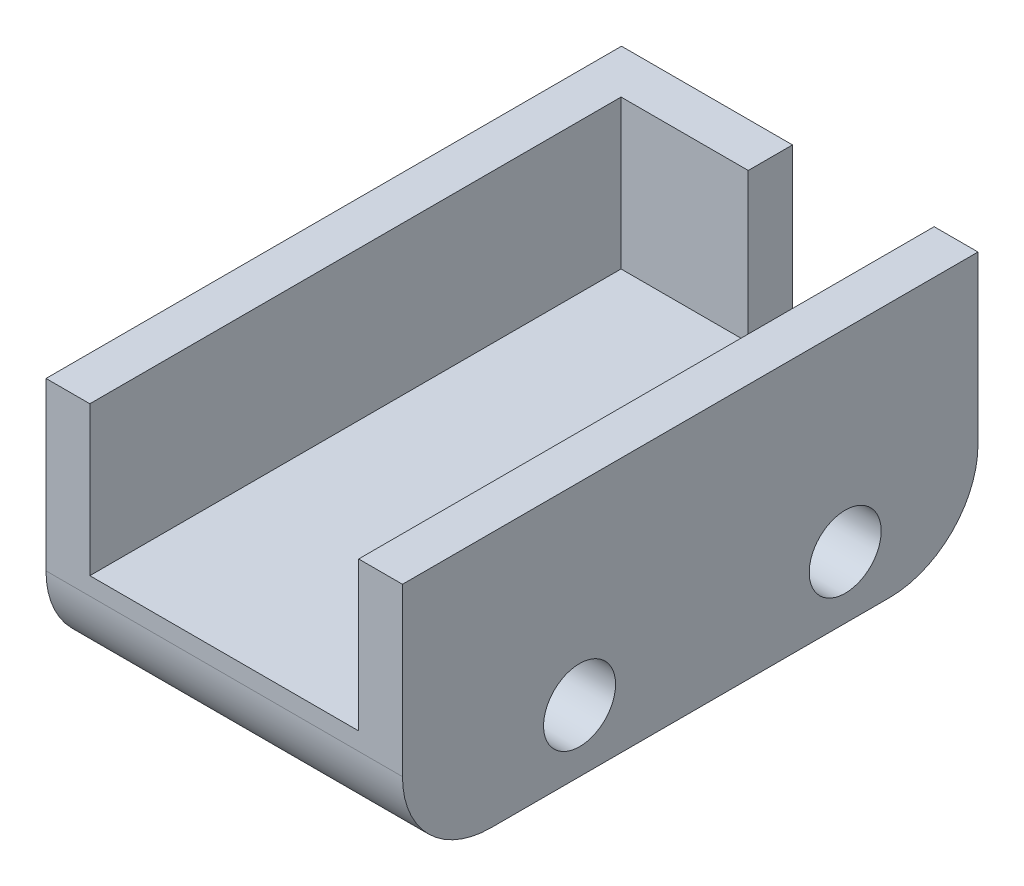
SolidWorks part; units mm, degrees
ref_plane "Plan de face" through (0, 0, 0) normal (0, 0, 1) x (1, 0, 0)
ref_plane "Plan de dessus" through (0, 0, 0) normal (0, 1, 0) x (1, 0, 0)
ref_plane "Plan de droite" through (0, 0, 0) normal (1, 0, 0) x (0, 0, -1)
sketch "Esquisse1" plane through (0, 0, 0) normal (0, 0, 1) x (1, 0, 0)
  line L1 (0, 0) -> (40.263, 0)
  line L2 (0, 0) -> (0, 26.8179)
  line L3 (0, 26.8179) -> (40.263, 26.8179)
  line L4 (40.263, 0) -> (40.263, 26.8179)
  dimension "D1" = 40.263
  dimension "D2" = 26.8179
extrude "Boss.-Extru.1" add sketch "Esquisse1" along normal blind 65 contours L2 L1 L4 L3
shell "Coque1" thickness 1.5
sketch "Esquisse4" plane through (0, 0, 0) normal (0, -1, 0) x (1, 0, 0)
  line L1 (0, 65) -> (40.263, 65)
  line L2 (0, 65) -> (0, 0)
  line L3 (0, 0) -> (40.263, 0)
  line L4 (40.263, 65) -> (40.263, 0)
extrude "Boss.-Extru.2" add sketch "Esquisse4" along normal blind 2
sketch "Esquisse5" plane through (40.263, 0, 0) normal (1, 0, 0) x (0, 0, -1)
  line L0 (0, -2) -> (-65, -2) construction
  line L1 (0, -2) -> (0, 26.8179) construction
  circle A0 centre (-15, 5) radius 4.065
  circle A1 centre (-45, 5) radius 4.065
  dimension "D3" = 8.13
  dimension "D1" = 7
  dimension "D2" = 15
  dimension "D4" = 30
extrude "Enlèv. mat.-Extru.3" cut sketch "Esquisse5" against normal through all
fillet "Congé2" radius 10 1 edges at (20.1315, -2, 0)
fillet "Congé3" radius 10 1 edges at (20.1315, -2, 65)
sketch "Esquisse6" plane through (0, 0, 5) normal (0, 0, 1) x (1, 0, 0)
  line L0 (4.95, 10) -> (35.313, 10) construction
  line L1 (35.313, 26.8179) -> (19.313, 26.8179)
  line L2 (35.313, 26.8179) -> (35.313, 10)
  line L3 (35.313, 10) -> (19.313, 10)
  line L4 (19.313, 26.8179) -> (19.313, 10)
  dimension "D1" = 16
extrude "Enlèv. mat.-Extru.4" cut sketch "Esquisse6" against normal through all
equation "\"1.5.00mm\"=2"
